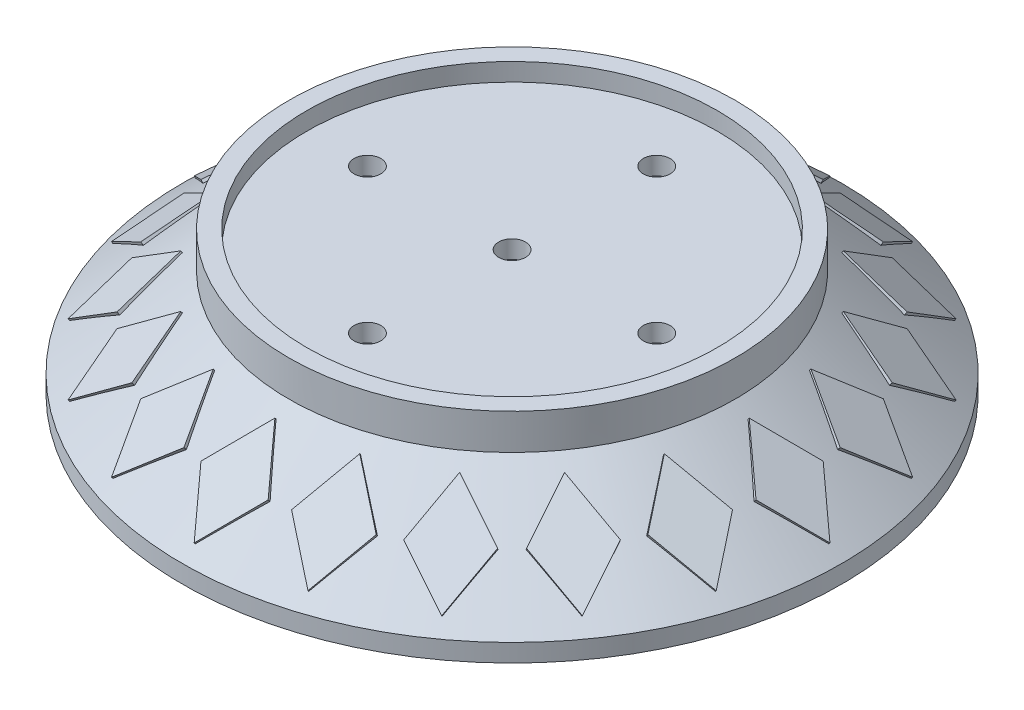
SolidWorks part; units mm, degrees
ref_plane "Front Plane" through (0, 0, 0) normal (0, 0, 1) x (1, 0, 0)
ref_plane "Top Plane" through (0, 0, 0) normal (0, 1, 0) x (1, 0, 0)
ref_plane "Right Plane" through (0, 0, 0) normal (1, 0, 0) x (0, 0, -1)
sketch "Sketch1" plane through (0, 0, 0) normal (0, 1, 0) x (1, 0, 0)
  line L0 (0, 0) -> (20.574, 0) construction
  line L1 (0, 0) -> (0, -20.574) construction
  line L2 (0, 0) -> (-20.574, 0) construction
  line L3 (0, 0) -> (0, 20.574) construction
  circle A0 centre (0, 0) radius 12.7 construction
  circle A1 centre (20.574, 0) radius 7.62 construction
  circle A2 centre (0, -20.574) radius 7.62 construction
  circle A3 centre (-20.574, 0) radius 7.62 construction
  circle A4 centre (0, 20.574) radius 7.62 construction
  circle A5 centre (0, 20.574) radius 1.905
  circle A6 centre (20.574, 0) radius 1.905
  circle A7 centre (0, -20.574) radius 1.905
  circle A8 centre (-20.574, 0) radius 1.905
  circle A9 centre (0, 0) radius 1.905
  circle A10 centre (0, 0) radius 31.75
  point P14 (0, 0)
  dimension "D1" = 25.4
  dimension "D2" = 15.24
  dimension "D4" = 3.81
  dimension "D5" = 63.5
  dimension ".81" = 20.574
  dimension "D3" = 4
extrude "Boss-Extrude1" add sketch "Sketch1" along normal blind 2.54
sketch "Sketch2" plane through (0, 2.54, 0) normal (0, 1, 0) x (1, 0, 0)
  circle A0 centre (0, 0) radius 31.75 construction
  circle A1 centre (0, 0) radius 31.75
  circle A2 centre (0, 0) radius 29.21
  dimension "D1" = 2.54
extrude "Boss-Extrude2" add sketch "Sketch2" along normal blind 2.54
sketch "Sketch3" plane through (0, 0, 0) normal (0, -1, 0) x (1, 0, 0)
  circle A1 centre (0, 0) radius 31.75
  circle A2 centre (0, 0) radius 31.75
  dimension "D1" = 0
extrude "Boss-Extrude3" add sketch "Sketch3" along normal blind 12.7 draft 50 draft outward yes
sketch "Sketch4" plane through (0, -12.7, 0) normal (0, -1, 0) x (1, 0, 0)
  circle A1 centre (0, 0) radius 46.8853
  circle A2 centre (0, 0) radius 46.8853
  dimension "D1" = 0
extrude "Boss-Extrude4" add sketch "Sketch4" along normal blind 2.54
sketch "Sketch5" plane through (0, 0, 0) normal (0, 0, 1) x (1, 0, 0)
  line L0 (-31.75, 0) -> (-46.8853, -12.7) construction
  line L1 (-31.75, 0) -> (-46.8853, -12.7) construction
  line L2 (-39.3176, -6.35) -> (-36.6913, -9.4799) construction
ref_plane "Plane1" through (-39.3176, -6.35, 0) normal (-0.6428, 0.766, 0) x (0.766, 0.6428, 0)
sketch "Sketch6" plane through (-39.3176, -6.35, 0) normal (-0.6428, 0.766, 0) x (0.766, 0.6428, 0)
  line L0 (-7.4977, 0) -> (0, -4.7766)
  line L1 (9.8788, 0) -> (-9.8788, 0) construction
  line L2 (0, -4.7766) -> (7.4977, 0)
  line L3 (7.4977, 0) -> (0, 4.7766)
  line L4 (0, 4.7766) -> (-7.4977, 0)
  line L5 (7.4977, 0) -> (9.8788, 0) construction
  line L6 (-7.4977, 0) -> (-9.8788, 0) construction
  ellipse E0 centre (34.2008, 0) end of major axis (34.2008, 31.75) minor radius 24.3219 construction
  ellipse E1 centre (26.0374, 0) end of major axis (26.0374, 46.8853) minor radius 35.9162 construction
  dimension "D1" = 115
  dimension "D2" = 8.89
extrude "Boss-Extrude5" add sketch "Sketch6" against normal blind 1.27 and the other way blind 0.254
pattern_circular "CirPattern1" count 20 over 360 about axis through (0, 0, 0) along (0, 1, 0) of "Boss-Extrude5"
